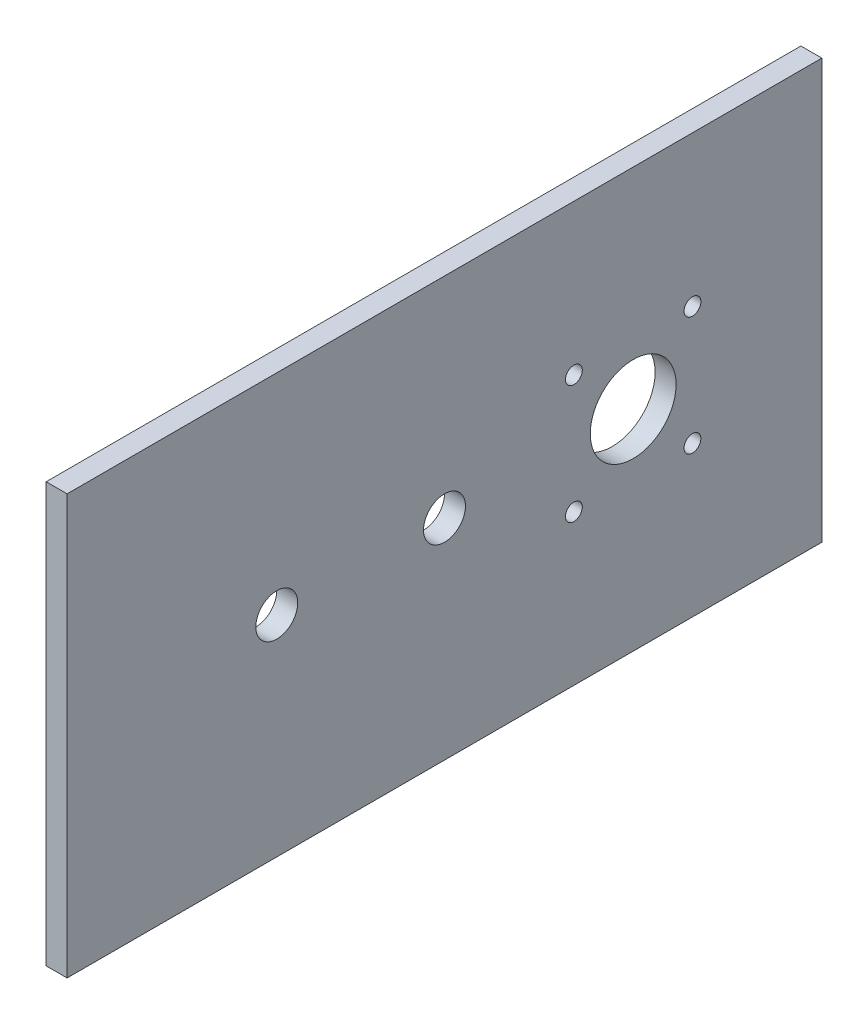
SolidWorks part; units mm, degrees
ref_plane "Front Plane" through (0, 0, 0) normal (0, 0, 1) x (1, 0, 0)
ref_plane "Top Plane" through (0, 0, 0) normal (0, 1, 0) x (1, 0, 0)
ref_plane "Right Plane" through (0, 0, 0) normal (1, 0, 0) x (0, 0, -1)
sketch "Sketch2" plane through (0, 0, 0) normal (1, 0, 0) x (0, 0, -1)
  line L1 (114.3, -63.5) -> (-114.3, -63.5)
  line L2 (114.3, -63.5) -> (114.3, 63.5)
  line L3 (114.3, 63.5) -> (-114.3, 63.5)
  line L4 (-114.3, -63.5) -> (-114.3, 63.5)
  line L5 (114.3, -63.5) -> (-114.3, 63.5) construction
  line L6 (114.3, 63.5) -> (-114.3, -63.5) construction
  circle A0 centre (-50.8, 0) radius 6.35
  circle A1 centre (57.15, 0) radius 13
  circle A2 centre (57.15, 0) radius 19.05 construction
  circle A3 centre (-50.8, 0) radius 25.4 construction
  circle A4 centre (0, 0) radius 6.35
  circle A5 centre (0, 0) radius 25.4 construction
  circle A6 centre (57.15, 0) radius 25.4 construction
  circle A7 centre (75.1105, 17.9605) radius 2.5527
  circle A8 centre (75.1105, -17.9605) radius 2.5527
  circle A9 centre (39.1895, -17.9605) radius 2.5527
  circle A10 centre (39.1895, 17.9605) radius 2.5527
  circle A11 centre (0, 0) radius 38.1 construction
  circle A12 centre (0, 0) radius 44.45 construction
  point P0 (0, 0)
  point P18 (47.0589, -4.816)
  point P20 (0, 0)
  point P27 (57.15, 0)
  point P28 (-53.1133, -5.0978)
  point P30 (55.59, -3.9904)
  point P31 (0, 0)
  point P32 (0, 0)
  point P33 (-123.0136, 62.3324)
  dimension "D1" = 12.7
  dimension "D3" = 26
  dimension "D4" = 38.1
  dimension "D7" = 5.1054
  dimension "D5" = 50.8
  dimension "D8" = 76.2
  dimension "D9" = 88.9
  dimension "D2" = 50.8
  dimension "D10" = 63.5
  dimension "D11" = 63.5
  dimension "D6" = 4
extrude "Boss-Extrude2" add sketch "Sketch2" along normal blind 6.35
equation "\"D3@Sketch2\"=25mm+1mm"
